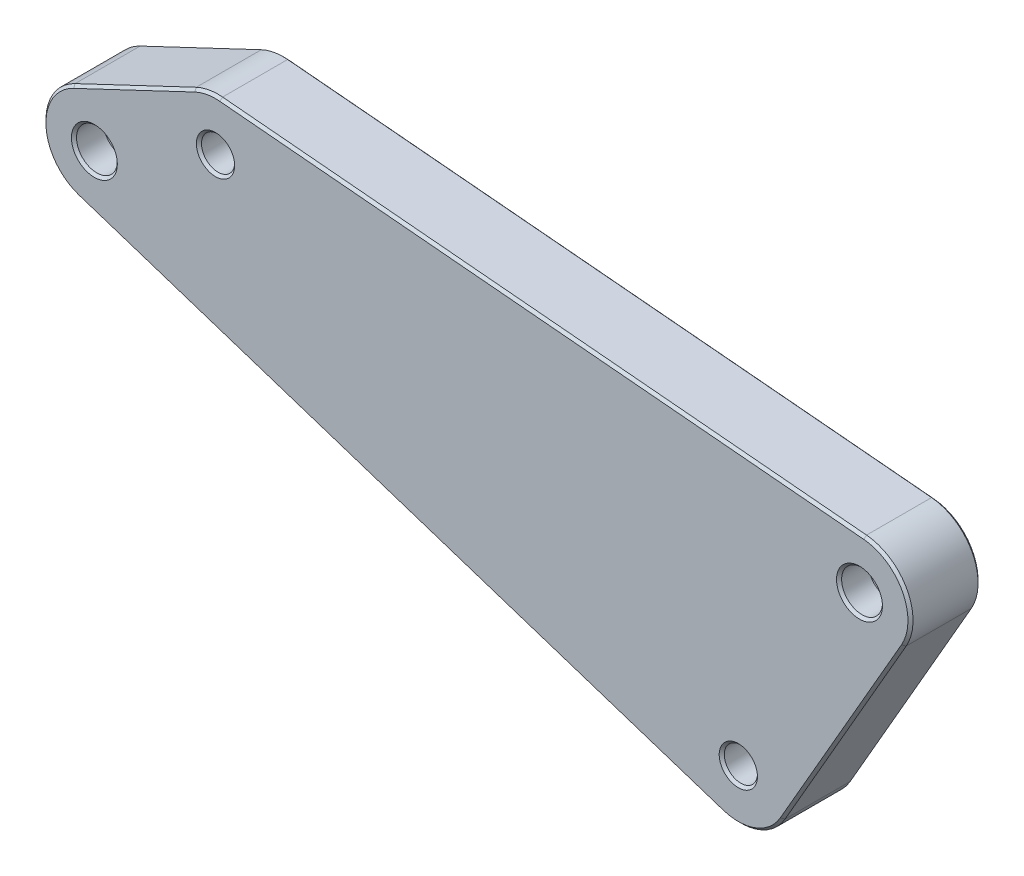
SolidWorks part; units mm, degrees
ref_plane "Front Plane" through (0, 0, 0) normal (0, 0, 1) x (1, 0, 0)
ref_plane "Top Plane" through (0, 0, 0) normal (0, 1, 0) x (1, 0, 0)
ref_plane "Right Plane" through (0, 0, 0) normal (1, 0, 0) x (0, 0, -1)
sketch "Sketch1" plane through (0, 0, 0) normal (0, 0, 1) x (1, 0, 0)
  line L0 (-20.145, 14.4842) -> (30.355, 9.9842)
  line L1 (-5.5616, 0) -> (3.8053, 0) construction
  line L2 (0, 17.119) -> (0, -12.4451) construction
  line L3 (33.4665, 4.0041) -> (23.9665, -12.4959)
  line L7 (-31.7123, 9.615) -> (-22.2123, 14.115)
  line L8 (-31.2423, 2.1978) -> (19.2577, -14.3022)
  circle A0 centre (-20.5, 10.5) radius 1.8 construction
  circle A1 centre (20.5, -10.5) radius 1.8 construction
  circle A2 centre (-20.5, 10.5) radius 1.8
  circle A3 centre (20.5, -10.5) radius 1.8
  circle A4 centre (-30, 6) radius 1.6
  circle A5 centre (-30, 6) radius 4
  circle A6 centre (-20.5, 10.5) radius 4
  circle A7 centre (20.5, -10.5) radius 4
  circle A8 centre (30, 6) radius 4
  circle A9 centre (30, 6) radius 1.6
  circle A10 centre (-20.5, 10.5) radius 1.3
  circle A11 centre (20.5, -10.5) radius 1.3
  dimension "D2" = 3.2
  dimension "D3" = 8
  dimension "D1" = 2.6
  dimension "D4" = 60
  dimension "D5" = 6
extrude "Boss-Extrude1" add sketch "Sketch1" along normal blind 5.5 contours L3 A8 L0 A6 L7 A5 L8 A7 | A5 A4 | A6 A2 | A8 A9 | A7 A3 | A2 A10 | A3 A11
sketch "Sketch2" plane through (0, 0, 0) normal (0, 0, 1) x (1, 0, 0)
  circle A0 centre (-30, 6) radius 2.8
  circle A1 centre (30, 6) radius 2.8
  dimension "D1" = 5.6
extrude "Cut-Extrude1" cut sketch "Sketch2" along normal blind 3.2
chamfer "Chamfer1" distance 0.2 angle 45 24 edges at (-19.2, 10.5, 5.5) (-19.2, 10.5, 0) (21.8, -10.5, 5.5) (21.8, -10.5, 0) (31.6, 6, 5.5) (-28.4, 6, 5.5) (21.9326, -14.2346, 0) (21.9326, -14.2346, 5.5) (-5.9923, -6.0522, 0) (-5.9923, -6.0522, 5.5) (-33.992, 5.747, 0) (-33.992, 5.747, 5.5) (-26.9623, 11.865, 0) (-26.9623, 11.865, 5.5) (-21.2033, 14.4377, 0) (-21.2033, 14.4377, 5.5) (5.105, 12.2342, 0) (5.105, 12.2342, 5.5) (33.5484, 7.8463, 0) (33.5484, 7.8463, 5.5) (28.7165, -4.2459, 0) (28.7165, -4.2459, 5.5) (32.8, 6, 0) (-27.2, 6, 0)
